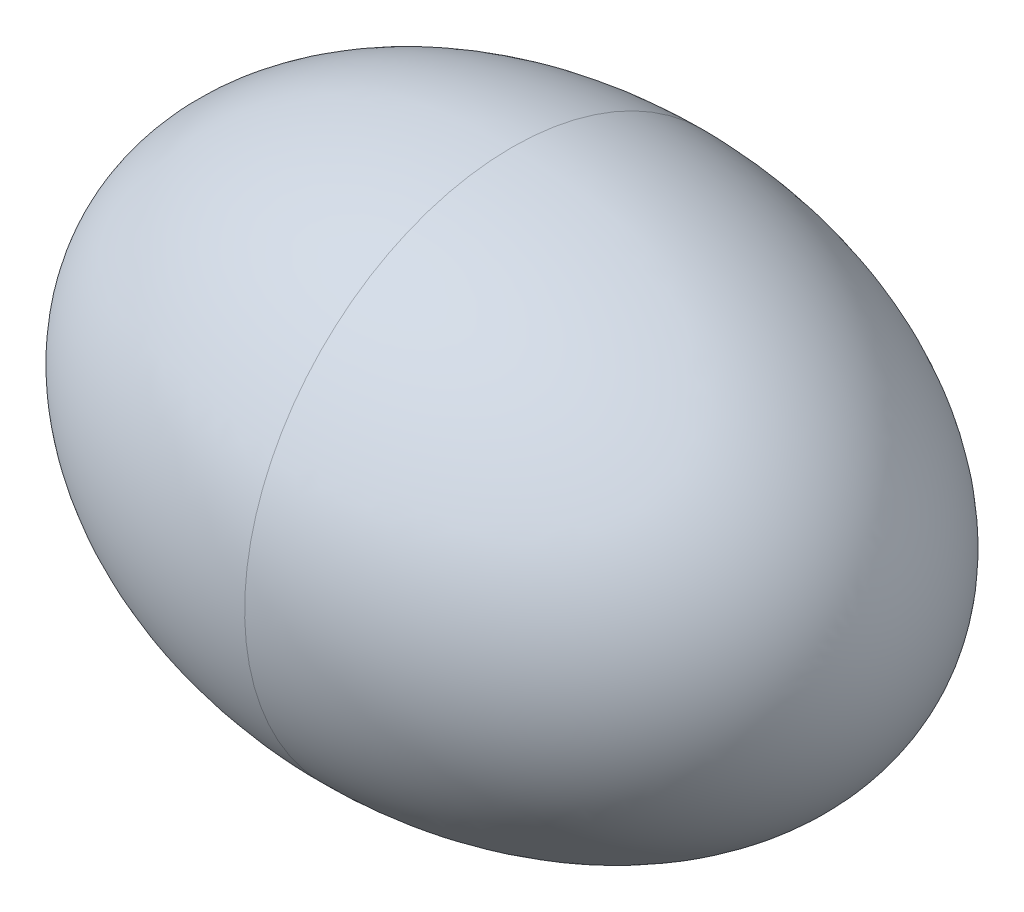
SolidWorks part; units mm, degrees
ref_plane "Front Plane" through (0, 0, 0) normal (0, 0, 1) x (1, 0, 0)
ref_plane "Top Plane" through (0, 0, 0) normal (0, 1, 0) x (1, 0, 0)
ref_plane "Right Plane" through (0, 0, 0) normal (1, 0, 0) x (0, 0, -1)
sketch "Sketch1" plane through (0, 0, 0) normal (0, 0, 1) x (1, 0, 0)
  line L0 (-57.9913, 0) -> (26.4171, 0) construction
  line L1 (0, 60.3593) -> (0, -20.7863) construction
  line L2 (31.75, 0) -> (-31.75, 0)
  spline S0 degree 4 poles (-3.1755, 22.1225) (-2.8715, 22.1437) (-2.2671, 22.1807) (-1.5084, 22.2152) (-0.4639, 22.2343) (0.2354, 22.2351) (0.9108, 22.2262) (1.5489, 22.2094) (2.318, 22.1778) (3.239, 22.123) (4.32, 22.0344) (5.5466, 21.8992) (7.0777, 21.6874) (8.5985, 21.4182) (10.1088, 21.0907) (11.9033, 20.6264) (13.6782, 20.0901) (15.4231, 19.4615) (17.1302, 18.7374) (18.8013, 17.9348) (20.4322, 17.0522) (22.0104, 16.0627) (23.5149, 14.9653) (24.7116, 13.9764) (25.6312, 13.1395) (26.5028, 12.2629) (27.3272, 11.3417) (28.0993, 10.3762) (28.8138, 9.3671) (29.4648, 8.316) (30.0465, 7.2248) (30.5528, 6.0966) (30.9779, 4.9353) (31.3434, 3.6507) (31.6138, 2.2674) (31.7241, 1.172) (31.75, 0.3825) (31.75, 0) knots 0 0 0 0 0 0.02631 0.052619 0.069219 0.082677 0.096135 0.109594 0.123052 0.149968 0.176884 0.2038 0.230717 0.284549 0.311466 0.338382 0.392214 0.446047 0.472963 0.499879 0.553712 0.607545 0.635098 0.662014 0.68893 0.715847 0.742763 0.769679 0.796595 0.82351 0.850427 0.877341 0.904255 0.931177 0.966689 1 1 1 1 1 construction
  spline S1 degree 4 poles (0, 22.2339) (0.1438, 22.2339) (0.4322, 22.2325) (0.9108, 22.2262) (1.5489, 22.2094) (2.318, 22.1778) (3.239, 22.123) (4.32, 22.0344) (5.5466, 21.8992) (7.0777, 21.6874) (8.5985, 21.4182) (10.1088, 21.0907) (11.9033, 20.6264) (13.6782, 20.0901) (15.4231, 19.4615) (17.1302, 18.7374) (18.8013, 17.9348) (20.4322, 17.0522) (22.0104, 16.0627) (23.5149, 14.9653) (24.7116, 13.9764) (25.6312, 13.1395) (26.5028, 12.2629) (27.3272, 11.3417) (28.0993, 10.3762) (28.8138, 9.3671) (29.4648, 8.316) (30.0465, 7.2248) (30.5528, 6.0966) (30.9779, 4.9353) (31.3434, 3.6507) (31.6138, 2.2674) (31.7241, 1.172) (31.75, 0.3825) (31.75, 0) knots 0.069219 0.069219 0.069219 0.069219 0.069219 0.082677 0.096135 0.109594 0.123052 0.149968 0.176884 0.2038 0.230717 0.284549 0.311466 0.338382 0.392214 0.446047 0.472963 0.499879 0.553712 0.607545 0.635098 0.662014 0.68893 0.715847 0.742763 0.769679 0.796595 0.82351 0.850427 0.877341 0.904255 0.931177 0.966689 1 1 1 1 1
  spline S2 degree 4 poles (0, 22.2339) (-0.1438, 22.2339) (-0.4322, 22.2325) (-0.9108, 22.2262) (-1.5489, 22.2094) (-2.318, 22.1778) (-3.239, 22.123) (-4.32, 22.0344) (-5.5466, 21.8992) (-7.0777, 21.6874) (-8.5985, 21.4182) (-10.1088, 21.0907) (-11.9033, 20.6264) (-13.6782, 20.0901) (-15.4231, 19.4615) (-17.1302, 18.7374) (-18.8013, 17.9348) (-20.4322, 17.0522) (-22.0104, 16.0627) (-23.5149, 14.9653) (-24.7116, 13.9764) (-25.6312, 13.1395) (-26.5028, 12.2629) (-27.3272, 11.3417) (-28.0993, 10.3762) (-28.8138, 9.3671) (-29.4648, 8.316) (-30.0465, 7.2248) (-30.5528, 6.0966) (-30.9779, 4.9353) (-31.3434, 3.6507) (-31.6138, 2.2674) (-31.7241, 1.172) (-31.75, 0.3825) (-31.75, 0) knots 0.069219 0.069219 0.069219 0.069219 0.069219 0.082677 0.096135 0.109594 0.123052 0.149968 0.176884 0.2038 0.230717 0.284549 0.311466 0.338382 0.392214 0.446047 0.472963 0.499879 0.553712 0.607545 0.635098 0.662014 0.68893 0.715847 0.742763 0.769679 0.796595 0.82351 0.850427 0.877341 0.904255 0.931177 0.966689 1 1 1 1 1
revolve "Revolve1" add sketch "Sketch1" angle 360 about L2
